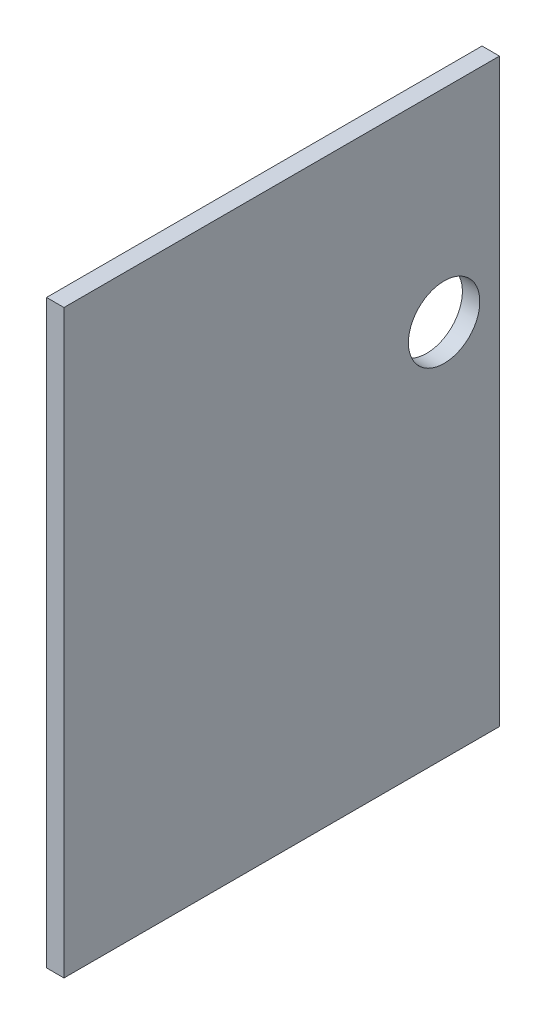
SolidWorks part; units mm, degrees
ref_plane "Front Plane" through (0, 0, 0) normal (0, 0, 1) x (1, 0, 0)
ref_plane "Top Plane" through (0, 0, 0) normal (0, 1, 0) x (1, 0, 0)
ref_plane "Right Plane" through (0, 0, 0) normal (1, 0, 0) x (0, 0, -1)
sketch "Sketch1" plane through (0, 0, 0) normal (1, 0, 0) x (0, 0, -1)
  line L0 (0, 0) -> (71.0293, 38.2951) construction
  line L1 (-95.25, -127) -> (95.25, -127)
  line L2 (-95.25, -127) -> (-95.25, 127)
  line L3 (-95.25, 127) -> (95.25, 127)
  line L4 (95.25, -127) -> (95.25, 127)
  line L5 (-95.25, -127) -> (95.25, 127) construction
  line L6 (-95.25, 127) -> (95.25, -127) construction
  circle A0 centre (71.0293, 38.2951) radius 15.621
  point P0 (0, 0)
  point P8 (57.8247, 0)
  point P9 (55.9665, 21.4198)
  point P10 (71.0293, 38.2951)
  dimension "D1" = 31.242
  dimension "D2" = 190.5
  dimension "D3" = 254
extrude "Boss-Extrude1" add sketch "Sketch1" along normal blind 7.62
